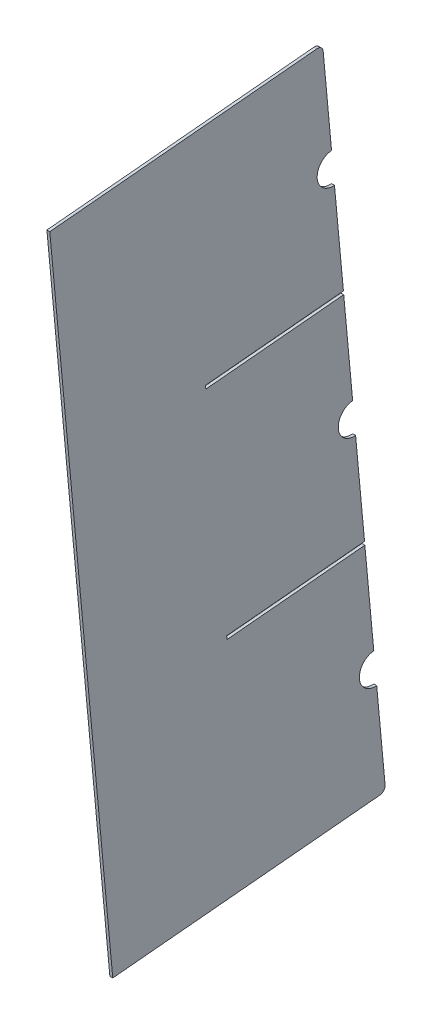
SolidWorks part; units mm, degrees
ref_plane "前视基准面" through (0, 0, 0) normal (0, 0, 1) x (1, 0, 0)
ref_plane "上视基准面" through (0, 0, 0) normal (0, 1, 0) x (1, 0, 0)
ref_plane "右视基准面" through (0, 0, 0) normal (1, 0, 0) x (0, 0, -1)
ref_plane "基准面1" through (-61.5, 0, 0) normal (-1, 0, 0) x (0, -1, 0)
sketch "草图1" plane through (-61.5, 0, 0) normal (-1, 0, 0) x (0, -1, 0)
  line L0 (145.113, 800.6032) -> (176.3784, 797.6987)
  line L1 (178.5548, 799.5051) -> (187.1573, 892.1064)
  line L2 (187.1573, 892.1064) -> (-47.8309, 913.9365)
  line L3 (-47.8309, 913.9365) -> (-56.4334, 821.3352)
  line L4 (-54.627, 819.1588) -> (-23.3616, 816.2543)
  line L5 (-12.4088, 815.2368) -> (20.8481, 812.1473)
  line L6 (20.8481, 812.1473) -> (25.2881, 859.9415)
  line L7 (25.2881, 859.9415) -> (26.4829, 859.8305)
  line L8 (26.4829, 859.8305) -> (22.0429, 812.0363)
  line L9 (22.0429, 812.0363) -> (55.3993, 808.9375)
  line L10 (66.3521, 807.92) -> (99.7085, 804.8212)
  line L11 (99.7085, 804.8212) -> (104.1485, 852.6154)
  line L12 (104.1485, 852.6154) -> (105.3434, 852.5044)
  line L13 (105.3434, 852.5044) -> (100.9033, 804.7102)
  line L14 (100.9033, 804.7102) -> (134.1602, 801.6207)
  arc A0 (176.3784, 797.6987) -> (178.5548, 799.5051) centre (176.5634, 799.6901) ccw
  arc A1 (-56.4334, 821.3352) -> (-54.627, 819.1588) centre (-54.442, 821.1502) ccw
  arc A2 (-23.3616, 816.2543) -> (-12.4088, 815.2368) centre (-17.8852, 815.7455) cw
  arc A3 (55.3993, 808.9375) -> (66.3521, 807.92) centre (60.8757, 808.4287) cw
  arc A4 (134.1602, 801.6207) -> (145.113, 800.6032) centre (139.6366, 801.112) cw
extrude "凸台-拉伸1" add sketch "草图1" against normal blind 1
